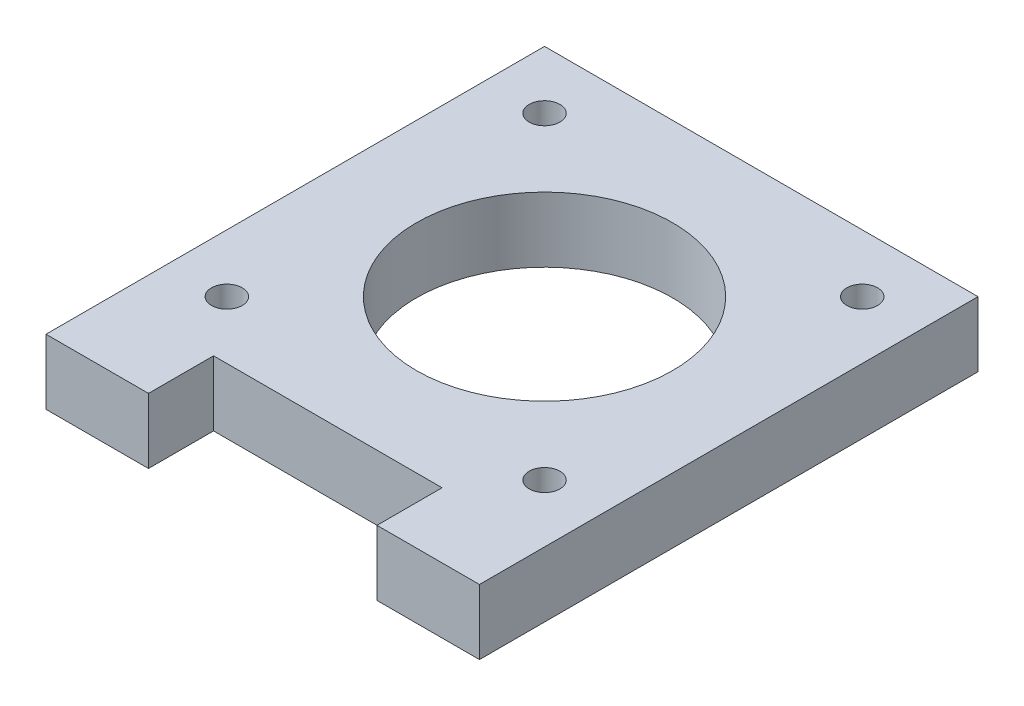
SolidWorks part; units mm, degrees
ref_plane "Front Plane" through (0, 0, 0) normal (0, 0, 1) x (1, 0, 0)
ref_plane "Top Plane" through (0, 0, 0) normal (0, 1, 0) x (1, 0, 0)
ref_plane "Right Plane" through (0, 0, 0) normal (1, 0, 0) x (0, 0, -1)
sketch "Sketch1" plane through (0, 0, 0) normal (0, 1, 0) x (1, 0, 0)
  line L0 (-21.15, -21.15) -> (-21.15, -27.5)
  line L1 (-15.5, -15.5) -> (15.5, -15.5) construction
  line L2 (-15.5, -15.5) -> (-15.5, 15.5) construction
  line L3 (-15.5, 15.5) -> (15.5, 15.5) construction
  line L4 (15.5, -15.5) -> (15.5, 15.5) construction
  line L5 (-15.5, -15.5) -> (15.5, 15.5) construction
  line L6 (-15.5, 15.5) -> (15.5, -15.5) construction
  line L7 (-21.15, -21.15) -> (21.15, -21.15) construction
  line L8 (-21.15, -21.15) -> (-21.15, 21.15)
  line L9 (-21.15, 21.15) -> (21.15, 21.15)
  line L10 (21.15, -21.15) -> (21.15, 21.15)
  line L11 (-21.15, -21.15) -> (21.15, 21.15) construction
  line L12 (-21.15, 21.15) -> (21.15, -21.15) construction
  line L13 (-21.15, -27.5) -> (-11.15, -27.5)
  line L14 (-11.15, -27.5) -> (-11.15, -21.15)
  line L15 (-11.15, -21.15) -> (11.15, -21.15)
  line L16 (11.15, -21.15) -> (11.15, -27.5)
  line L17 (11.15, -27.5) -> (21.15, -27.5)
  line L18 (21.15, -27.5) -> (21.15, -21.15)
  circle A0 centre (0, 0) radius 12.5
  circle A1 centre (-15.5, 15.5) radius 1.5
  circle A2 centre (15.5, 15.5) radius 1.5
  circle A3 centre (15.5, -15.5) radius 1.5
  circle A4 centre (-15.5, -15.5) radius 1.5
  point P0 (0, 0)
  dimension "D2" = 3
  dimension "D3" = 25
  dimension "D1" = 31
  dimension "D4" = 42.3
  dimension "D5" = 6.35
  dimension "D6" = 10
extrude "Boss-Extrude1" add sketch "Sketch1" along normal mid plane 6.35
